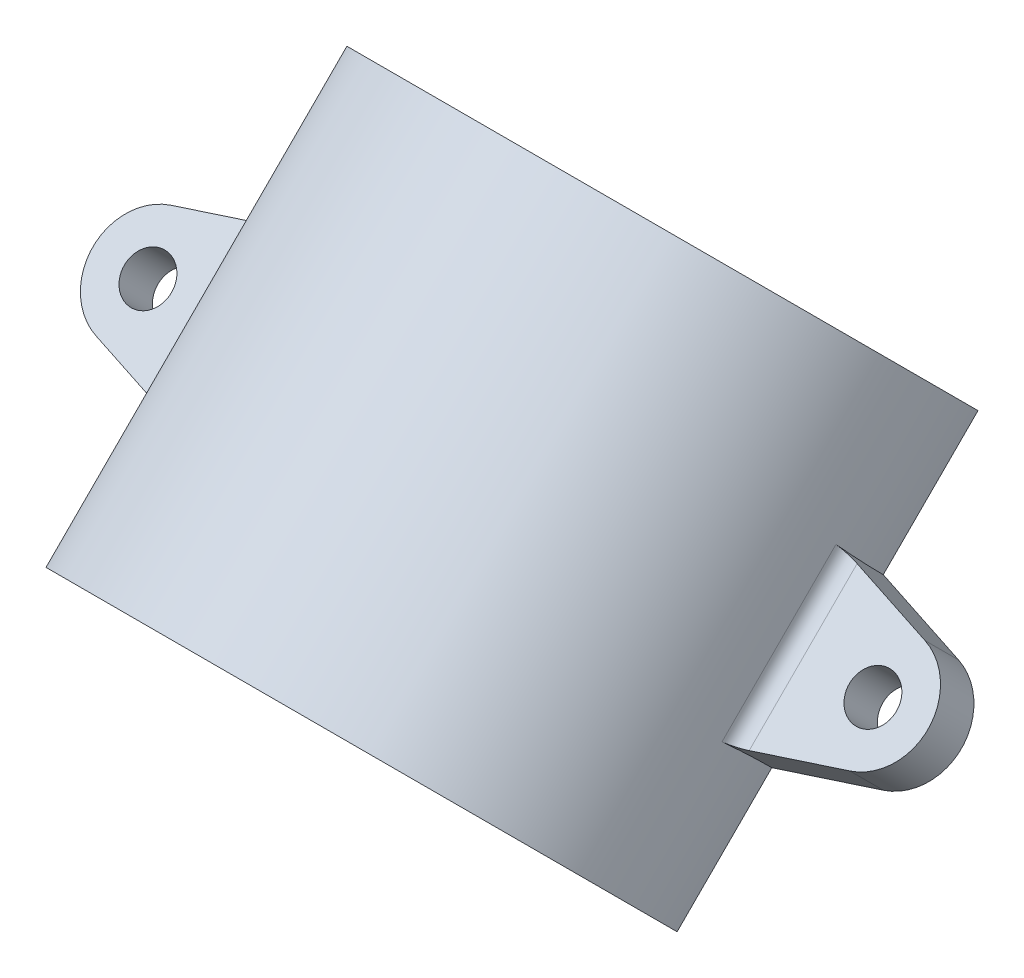
SolidWorks part; units mm, degrees
material "ABS"
ref_plane "Front Plane" through (0, 0, 0) normal (0, 0, 1) x (1, 0, 0)
ref_plane "Top Plane" through (0, 0, 0) normal (0, 1, 0) x (1, 0, 0)
ref_plane "Right Plane" through (0, 0, 0) normal (1, 0, 0) x (0, 0, -1)
sketch "Sketch1" plane through (0, 64.2244, -64.2244) normal (0, 0.7071, -0.7071) x (1, 0, 0)
  line L0 (91.8446, -130.5511) -> (88.8446, -130.5511)
  line L1 (58.8446, -130.5511) -> (55.8446, -130.5511)
  circle A0 centre (73.8446, -130.5511) radius 15 construction
  arc A1 (58.8446, -130.5511) -> (88.8446, -130.5511) centre (73.8446, -130.5511) ccw
  arc A2 (55.8446, -130.5511) -> (91.8446, -130.5511) centre (73.8446, -130.5511) ccw
  circle A3 centre (73.8446, -130.5511) radius 18 construction
  circle A4 centre (73.8446, -130.5511) radius 15 construction
  dimension "D1" = 3
extrude "Boss-Extrude1" add sketch "Sketch1" against normal up to surface (27 mm away)
sketch "Sketch2" plane through (0, 92.3136, 92.3136) normal (0, 0.7071, 0.7071) x (1, 0, 0)
  line L0 (97.77, 80.7025) -> (91.8446, 82.3271) construction
  line L1 (91.8446, 72.3271) -> (97.77, 73.9516) construction
  line L2 (49.9192, 73.9516) -> (55.8446, 72.3271) construction
  line L3 (55.8446, 82.3271) -> (49.9192, 80.7025) construction
  line L4 (97.77, 80.7025) -> (88.8446, 83.1496)
  line L5 (88.8446, 71.5046) -> (97.77, 73.9516)
  line L6 (49.9192, 73.9516) -> (58.8446, 71.5046)
  line L7 (58.8446, 83.1496) -> (49.9192, 80.7025)
  line L12 (58.8446, 71.5046) -> (58.8446, 83.1496)
  line L13 (88.8446, 71.5046) -> (88.8446, 83.1496)
  arc A0 (97.77, 73.9516) -> (97.77, 80.7025) centre (96.8446, 77.3271) ccw construction
  circle A1 centre (96.8446, 77.3271) radius 1.5 construction
  circle A2 centre (50.8446, 77.3271) radius 1.5 construction
  arc A3 (49.9192, 80.7025) -> (49.9192, 73.9516) centre (50.8446, 77.3271) ccw construction
  arc A4 (97.77, 73.9516) -> (97.77, 80.7025) centre (96.8446, 77.3271) ccw
  circle A5 centre (96.8446, 77.3271) radius 1.5
  circle A6 centre (50.8446, 77.3271) radius 1.5
  arc A7 (49.9192, 80.7025) -> (49.9192, 73.9516) centre (50.8446, 77.3271) ccw
extrude "Boss-Extrude2" add sketch "Sketch2" along normal blind 3
fillet "Fillet1" radius 1 2 edges at (56.0964, 149.1134, 39.7564) (91.5928, 149.1134, 39.7564)
